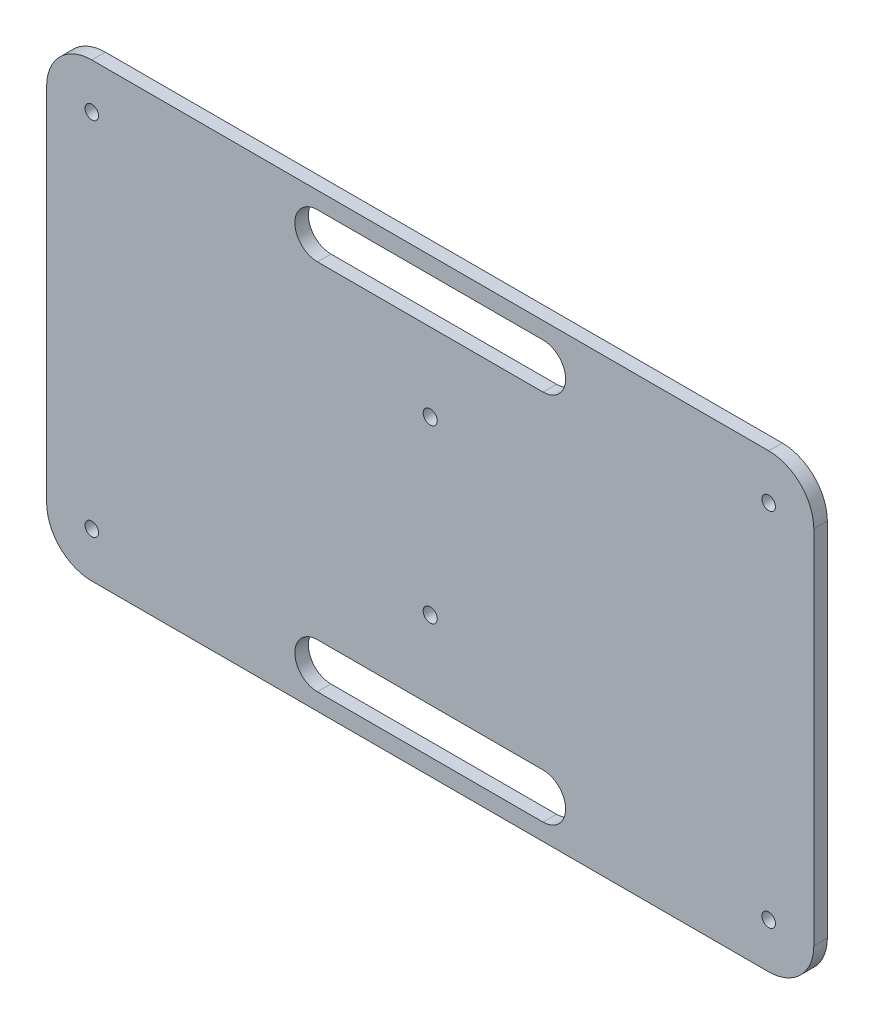
SolidWorks part; units mm, degrees
ref_plane "Front Plane" through (0, 0, 0) normal (0, 0, 1) x (1, 0, 0)
ref_plane "Top Plane" through (0, 0, 0) normal (0, 1, 0) x (1, 0, 0)
ref_plane "Right Plane" through (0, 0, 0) normal (1, 0, 0) x (0, 0, -1)
sketch "Sketch1" plane through (0, 0, 0) normal (0, 0, 1) x (1, 0, 0)
  line L0 (-85, 0) -> (85, 0) construction
  line L1 (-75, 50) -> (75, 50)
  line L2 (-85, 40) -> (-85, -40)
  line L3 (-75, -50) -> (75, -50)
  line L4 (85, 40) -> (85, -40)
  line L5 (-85, 50) -> (85, -50) construction
  line L6 (-85, -50) -> (85, 50) construction
  line L7 (0, 50) -> (0, -50) construction
  line L8 (-25, 41.2578) -> (25, 41.2578) construction
  line L9 (-25, 46.2578) -> (25, 46.2578)
  line L10 (-25, 36.2578) -> (25, 36.2578)
  line L11 (-25, -41.2578) -> (25, -41.2578) construction
  line L12 (-25, -46.2578) -> (25, -46.2578)
  line L13 (-25, -36.2578) -> (25, -36.2578)
  line L14 (0, 19) -> (0, -19) construction
  arc A0 (-25, 46.2578) -> (-25, 36.2578) centre (-25, 41.2578) ccw
  arc A1 (25, 36.2578) -> (25, 46.2578) centre (25, 41.2578) ccw
  arc A2 (-25, -46.2578) -> (-25, -36.2578) centre (-25, -41.2578) cw
  arc A3 (25, -36.2578) -> (25, -46.2578) centre (25, -41.2578) cw
  arc A20 (75, 50) -> (85, 40) centre (75, 40) cw
  arc A21 (85, -40) -> (75, -50) centre (75, -40) cw
  arc A22 (-75, -50) -> (-85, -40) centre (-75, -40) cw
  arc A23 (-75, 50) -> (-85, 40) centre (-75, 40) ccw
  circle A28 centre (-75, 40) radius 1.5
  circle A29 centre (75, 40) radius 1.5
  circle A30 centre (75, -40) radius 1.5
  circle A31 centre (-75, -40) radius 1.5
  circle A32 centre (0, 19) radius 1.56
  circle A33 centre (0, -19) radius 1.56
  point P0 (0, 0)
  point P12 (0, 41.2578)
  point P19 (0, -41.2578)
  point P27 (0, 0)
  dimension "D3" = 5
  dimension "D11" = 40
  dimension "D14" = 150
  dimension "D31" = 10
  dimension "D7" = 3.12
  dimension "D10" = 3
  dimension "D12" = 3
  dimension "D8" = 3.12
  dimension "D1" = 170
  dimension "D2" = 100
  dimension "D4" = 50
  dimension "D5" = 41.2578
  dimension "D6" = 38
  dimension "D9" = 75
  dimension "D13" = 80
  dimension "D15" = 150
extrude "Boss-Extrude1" add sketch "Sketch1" along normal blind 3
